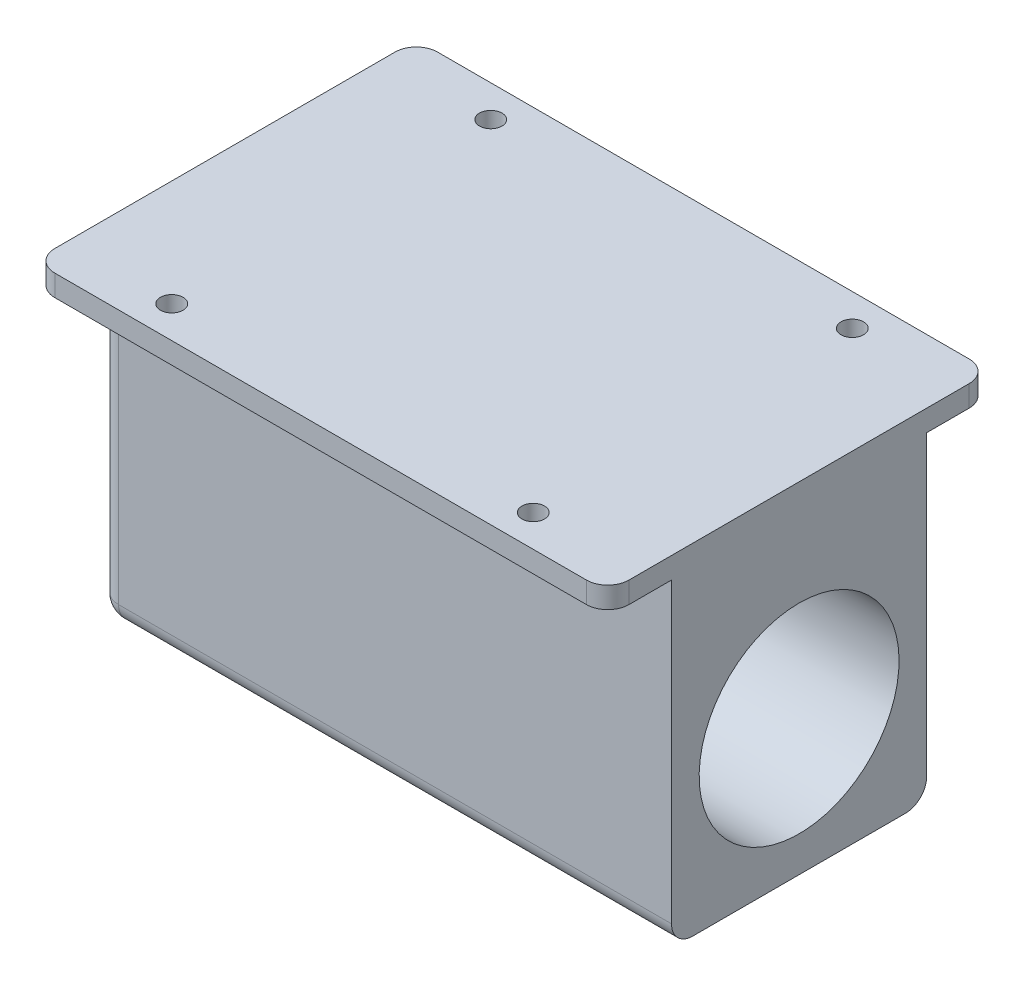
SolidWorks part; units mm, degrees
ref_plane "前视基准面" through (0, 0, 0) normal (0, 0, 1) x (1, 0, 0)
ref_plane "上视基准面" through (0, 0, 0) normal (0, 1, 0) x (1, 0, 0)
ref_plane "右视基准面" through (0, 0, 0) normal (1, 0, 0) x (0, 0, -1)
sketch "草图1" plane through (0, 0, 0) normal (0, 0, 1) x (1, 0, 0)
  line L0 (0, 0) -> (135, 0)
  line L1 (0, 0) -> (0, -80)
  line L2 (0, -80) -> (135, -80)
  line L6 (135, -80) -> (135, 0)
  dimension "D2" = 80
  dimension "D3" = 135
extrude "凸台-拉伸1" add sketch "草图1" along normal blind 60
sketch "草图2" plane through (0, 0, 60) normal (0, 0, 1) x (1, 0, 0)
  line L4 (24.1086, -76.68) -> (13.8, -76.68)
  line L5 (13.8, -76.68) -> (13.8, -19.68)
  line L6 (13.8, -19.68) -> (68.3, -19.68)
  line L7 (68.3, -19.68) -> (68.3, -76.68)
  line L8 (68.3, -76.68) -> (24.1086, -76.68)
  dimension "D3" = 57
  dimension "D4" = 54.5
extrude "切除-拉伸1" cut sketch "草图2" against normal blind 57 from offset 1.5 offset against normal yes
sketch "草图4" plane through (135, 0, 0) normal (1, 0, 0) x (0, 0, -1)
  line L0 (-30, -80) -> (-30, -48.18) construction
  line L1 (-60, -80) -> (0, -80) construction
  circle A0 centre (-30, -48.18) radius 23.5
  dimension "D2" = 47
  dimension "D1" = 31.82
extrude "切除-拉伸2" cut sketch "草图4" against normal up to next
sketch "草图5" plane through (0, 0, 0) normal (0, 1, 0) x (1, 0, 0)
  line L0 (0, 0) -> (135, 0)
  line L1 (135, 0) -> (135, 15)
  line L2 (135, 15) -> (0, 15)
  line L3 (0, 15) -> (0, 0)
  line L4 (135, -30) -> (120.0497, -30) construction
  line L5 (135, -60) -> (135, 0) construction
  line L6 (135, -75) -> (0, -75)
  line L7 (135, -60) -> (135, -75)
  line L8 (0, -60) -> (135, -60)
  line L9 (0, -75) -> (0, -60)
  dimension "D1" = 15
extrude "凸台-拉伸2" add sketch "草图5" against normal blind 5
sketch "草图6" plane through (0, -5, 0) normal (0, -1, 0) x (1, 0, 0)
  line L0 (0, 67.5) -> (25, 67.5) construction
  line L1 (0, 60) -> (0, 75) construction
  line L2 (67.5, 75) -> (67.5, 65.6257) construction
  line L3 (0, 75) -> (135, 75) construction
  line L4 (0, 30) -> (16.4214, 30) construction
  line L5 (0, 60) -> (0, 0) construction
  line L6 (135, 67.5) -> (110, 67.5) construction
  line L7 (135, -7.5) -> (110, -7.5) construction
  line L8 (0, -7.5) -> (25, -7.5) construction
  dimension "D1" = 25
hole_wizard "M5 六角头螺栓C级的柱形沉头孔1" positions "草图9" profile "草图8" counterbore size "M5" standard "GB"
sketch "草图9" plane through (0, -5, 0) normal (0, -1, 0) x (-1, 0, 0)
  point P0 (-110, 7.5)
  point P3 (-25, 7.5)
  point P6 (-110, -67.5)
  point P9 (-25, -67.5)
sketch "草图8" plane through (110, -5, -7.5) normal (1, 0, 0) x (0, 0, -1)
  line L0 (0, 0) -> (0, 6.7923)
  line L1 (0, 6.7923) -> (2.65, 5.2)
  line L2 (2.65, 5.2) -> (2.65, 0.5)
  line L3 (2.65, 0.5) -> (5.5, 0.5)
  line L4 (5.5, 0.5) -> (5.5, 0)
  line L5 (5.5, 0) -> (0, 0)
  line L10 (0, 6.7923) -> (-2.65, 5.2) construction
  line L11 (0, -6.35) -> (0, 107.95) construction
  dimension "孔直径" = 5.3
  dimension "孔深度" = 5.2
  dimension "柱形沉头孔直径" = 11
  dimension "柱形沉头孔深度" = 0.5
  dimension "导头角度" = 118
fillet "圆角1" radius 5 2 edges at (0, -42.5, 60) (0, -42.5, 0)
fillet "圆角2" radius 5 5 edges at (70, -80, 60) (1.4645, -80, 58.5355) (70, -80, 0) (1.4645, -80, 1.4645) (0, -80, 30)
fillet "圆角3" radius 5 4 edges at (135, -2.5, 75) (135, -2.5, -15) (0, -2.5, -15) (0, -2.5, 75)
